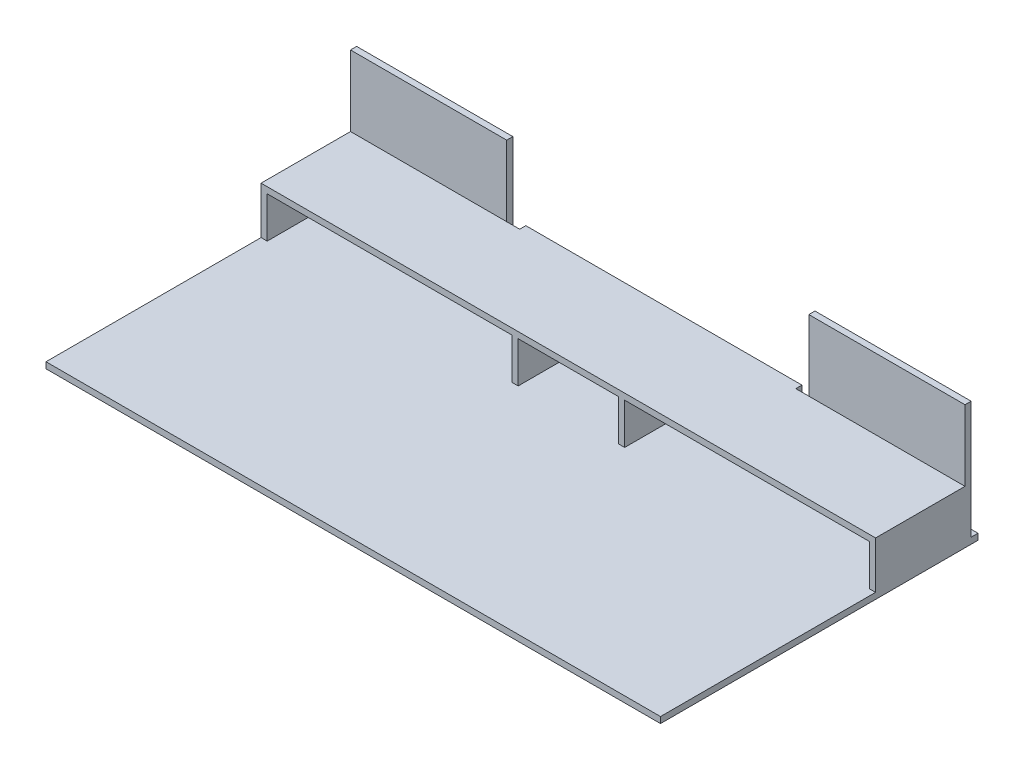
SolidWorks part; units mm, degrees
ref_plane "Front Plane" through (0, 0, 0) normal (0, 0, 1) x (1, 0, 0)
ref_plane "Top Plane" through (0, 0, 0) normal (0, 1, 0) x (1, 0, 0)
ref_plane "Right Plane" through (0, 0, 0) normal (1, 0, 0) x (0, 0, -1)
sketch "Sketch1" plane through (0, 0, 0) normal (0, 1, 0) x (1, 0, 0)
  line L1 (600, -310) -> (-600, -310)
  line L2 (600, -310) -> (600, 310)
  line L3 (600, 310) -> (-600, 310)
  line L4 (-600, -310) -> (-600, 310)
  line L5 (600, -310) -> (-600, 310) construction
  line L6 (600, 310) -> (-600, -310) construction
  point P0 (0, 0)
  dimension "D1" = 1200
  dimension "D2" = 620
extrude "Boss-Extrude1" add sketch "Sketch1" along normal blind 12
sketch "Sketch2" plane through (0, 12, 0) normal (0, 1, 0) x (1, 0, 0)
  line L0 (0, 310) -> (0, 0) construction
  line L1 (-600, 310) -> (-588, 310)
  line L2 (-600, 310) -> (-600, 110)
  line L3 (-600, 110) -> (-588, 110)
  line L4 (-588, 310) -> (-588, 110)
  line L5 (600, 310) -> (-600, 310) construction
  line L6 (98, 310) -> (98, 110)
  line L7 (-110, 310) -> (-98, 310)
  line L8 (-110, 310) -> (-110, 110)
  line L9 (-110, 110) -> (-98, 110)
  line L10 (-98, 310) -> (-98, 110)
  line L11 (110, 110) -> (98, 110)
  line L12 (110, 310) -> (110, 110)
  line L13 (110, 310) -> (98, 310)
  line L14 (588, 310) -> (588, 110)
  line L15 (600, 110) -> (588, 110)
  line L16 (600, 310) -> (600, 110)
  line L17 (600, 310) -> (588, 310)
  line L18 (-600, 284.6) -> (600, 284.6)
  line M10 (600, -310) -> (600, 310)
  dimension "D1" = 12
  dimension "D2" = 200
  dimension "D3" = 12
  dimension "D4" = 490
  dimension "D5" = 25.4
extrude "Boss-Extrude2" add sketch "Sketch2" along normal blind 80 contours L18 L2 L3 L4 | L18 L8 L9 L10 | L18 L6 L11 L12 | L18 L14 L15 M10
sketch "Sketch6" plane through (0, 92, 0) normal (0, 1, 0) x (1, 0, 0)
  line L1 (-600, 284.6) -> (600, 284.6)
  line L2 (-600, 284.6) -> (-600, 110)
  line L3 (-600, 110) -> (600, 110)
  line L4 (600, 284.6) -> (600, 110)
extrude "Boss-Extrude5" add sketch "Sketch6" along normal blind 12
sketch "Sketch7" plane through (0, 12, 0) normal (0, 1, 0) x (1, 0, 0)
  line L1 (-600, 284.6) -> (-295, 284.6)
  line L2 (-600, 284.6) -> (-600, 296.6)
  line L3 (-600, 296.6) -> (-295, 296.6)
  line L4 (-295, 284.6) -> (-295, 296.6)
  line L5 (600, 284.6) -> (295, 284.6)
  line L6 (600, 284.6) -> (600, 296.6)
  line L7 (600, 296.6) -> (295, 296.6)
  line L8 (295, 284.6) -> (295, 296.6)
  dimension "D1" = 12
  dimension "D2" = 305
  dimension "D3" = 12
  dimension "D4" = 305
extrude "Boss-Extrude6" add sketch "Sketch7" along normal blind 230
sketch "Sketch8" plane through (0, 0, -284.6) normal (0, 0, -1) x (-1, 0, 0)
  line L0 (-295, 104) -> (295, 104) construction
  line L1 (-269.6, 104) -> (269.6, 104)
  line L2 (-269.6, 104) -> (-269.6, 69)
  line L3 (-269.6, 69) -> (269.6, 69)
  line L4 (269.6, 104) -> (269.6, 69)
  line L5 (-295, 242) -> (-295, 12) construction
  line L6 (295, 242) -> (295, 12) construction
  dimension "D1" = 25.4
  dimension "D2" = 25.4
  dimension "D3" = 35
extrude "Boss-Extrude7" add sketch "Sketch8" along normal blind 12
